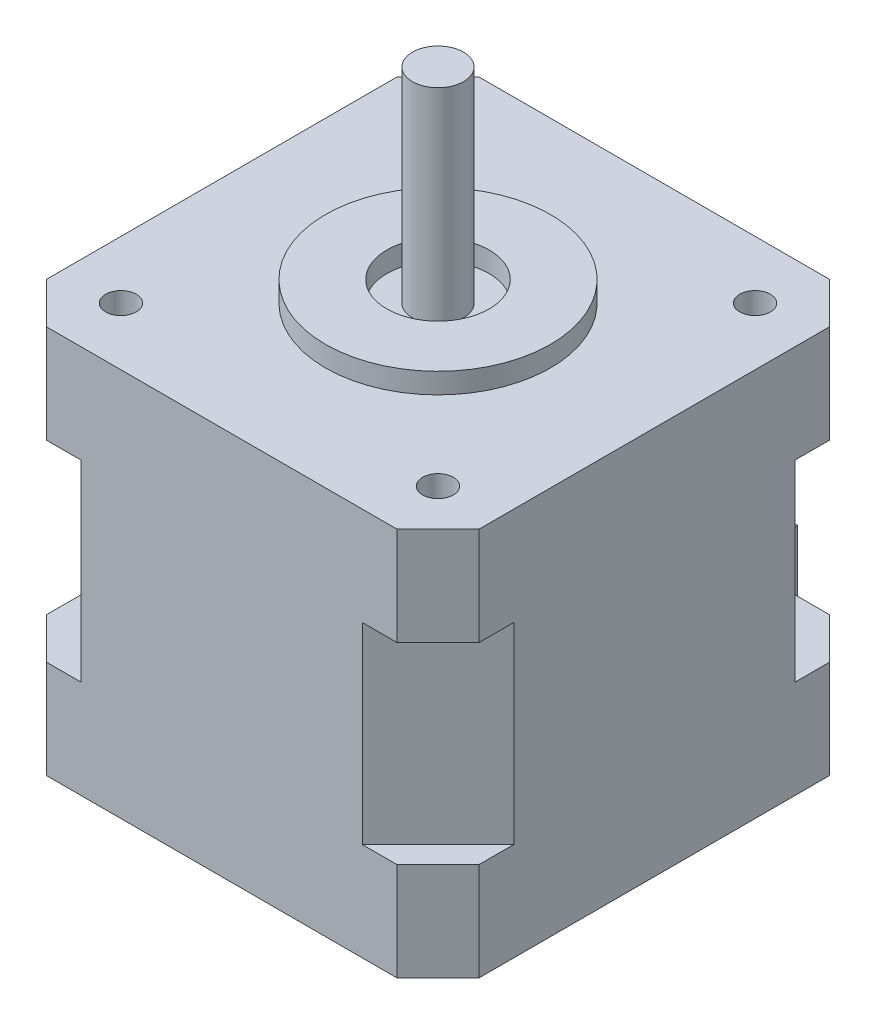
SolidWorks part; units mm, degrees
ref_plane "Front Plane" through (0, 0, 0) normal (0, 0, 1) x (1, 0, 0)
ref_plane "Top Plane" through (0, 0, 0) normal (0, 1, 0) x (1, 0, 0)
ref_plane "Right Plane" through (0, 0, 0) normal (1, 0, 0) x (0, 0, -1)
sketch "Sketch1" plane through (0, 0, 0) normal (0, 1, 0) x (1, 0, 0)
  line L1 (21.15, -21.15) -> (-21.15, -21.15)
  line L2 (21.15, -21.15) -> (21.15, 21.15)
  line L3 (21.15, 21.15) -> (-21.15, 21.15)
  line L4 (-21.15, -21.15) -> (-21.15, 21.15)
  line L5 (21.15, -21.15) -> (-21.15, 21.15) construction
  line L6 (21.15, 21.15) -> (-21.15, -21.15) construction
  point P0 (0, 0)
  dimension "D1" = 42.3
extrude "Boss-Extrude1" add sketch "Sketch1" along normal blind 9.6
chamfer "Chamfer1" distance 4 angle 45 4 edges at (21.15, 4.8, -21.15) (21.15, 4.8, 21.15) (-21.15, 4.8, 21.15) (-21.15, 4.8, -21.15)
sketch "Sketch2" plane through (0, 9.6, 0) normal (0, 1, 0) x (1, 0, 0)
  line L29 (-17.15, -21.15) -> (17.15, -21.15) construction
  line L31 (13.75, -21.15) -> (21.15, -13.7432)
  line L32 (21.15, -17.15) -> (21.15, 17.15) construction
  line L33 (0, 0) -> (0, -21.15) construction
  line L34 (0, 0) -> (-21.15, 0) construction
  line L35 (-21.15, 17.15) -> (-21.15, -17.15) construction
  line L36 (-13.75, -21.15) -> (-21.15, -13.7432)
  line L37 (-13.75, 21.15) -> (-21.15, 13.7432)
  line L38 (13.75, 21.15) -> (21.15, 13.7432)
  line L39 (13.75, -21.15) -> (-13.75, -21.15)
  line L40 (-21.15, -13.7432) -> (-21.15, 13.7432)
  line L41 (-13.75, 21.15) -> (13.75, 21.15)
  line L42 (21.15, 13.7432) -> (21.15, -13.7432)
  dimension "D1" = 13.75
  dimension "D2" = 10.47
extrude "Boss-Extrude2" add sketch "Sketch2" along normal blind 18.8
sketch "Sketch3" plane through (0, 28.4, 0) normal (0, 1, 0) x (1, 0, 0)
  line L8 (17.15, 21.15) -> (-17.15, 21.15)
  line L9 (21.15, 17.15) -> (17.15, 21.15)
  line L10 (21.15, -17.15) -> (21.15, 17.15)
  line L11 (17.15, -21.15) -> (21.15, -17.15)
  line L12 (-17.15, -21.15) -> (17.15, -21.15)
  line L13 (-21.15, -17.15) -> (-17.15, -21.15)
  line L14 (-21.15, 17.15) -> (-21.15, -17.15)
  line L15 (-17.15, 21.15) -> (-21.15, 17.15)
  line L16 (17.15, 21.15) -> (-17.15, 21.15)
  line L17 (21.15, 17.15) -> (17.15, 21.15)
  line L18 (21.15, -17.15) -> (21.15, 17.15)
  line L19 (17.15, -21.15) -> (21.15, -17.15)
  line L20 (-17.15, -21.15) -> (17.15, -21.15)
  line L21 (-21.15, -17.15) -> (-17.15, -21.15)
  line L22 (-21.15, 17.15) -> (-21.15, -17.15)
  line L23 (-17.15, 21.15) -> (-21.15, 17.15)
  dimension "D1" = 0
extrude "Boss-Extrude3" add sketch "Sketch3" along normal blind 9.6
sketch "Sketch4" plane through (0, 38, 0) normal (0, 1, 0) x (1, 0, 0)
  circle A0 centre (0, 0) radius 11
  circle A1 centre (0, 0) radius 5
  dimension "D1" = 22
  dimension "D2" = 10
extrude "Boss-Extrude4" add sketch "Sketch4" along normal blind 2
sketch "Sketch5" plane through (0, 38, 0) normal (0, 1, 0) x (1, 0, 0)
  circle A0 centre (0, 0) radius 2.5
extrude "Boss-Extrude5" add sketch "Sketch5" along normal blind 20
sketch "Sketch8" plane through (0, 38, 0) normal (0, 1, 0) x (1, 0, 0)
  line L0 (0, -23.2651) -> (0, 23.2651) construction
  line L1 (-23.2651, 0) -> (23.2651, 0) construction
  circle A0 centre (15.5, -15.5) radius 1.5
  dimension "D3" = 3
  dimension "D1" = 15.5
  dimension "D2" = 15.5
extrude "Cut-Extrude1" cut sketch "Sketch8" against normal blind 4
mirror "Mirror1" about plane through (0, 0, 0) normal (0, 0, 1) of "Cut-Extrude1"
mirror "Mirror2" about plane through (0, 0, 0) normal (1, 0, 0) of "Mirror1", "Cut-Extrude1"
ref_plane "Plane1" through (0, 19, 0) normal (0, 1, 0) x (1, 0, 0)
mirror "Mirror3" about plane through (0, 19, 0) normal (0, 1, 0) of "Mirror1", "Cut-Extrude1", "Mirror2"
sketch "Sketch9" plane through (0, 0, -21.15) normal (0, 0, -1) x (-1, 0, 0)
  line L0 (0, 23.2651) -> (0, -23.2651) construction
  line L1 (-8, 0) -> (8, 0)
  line L2 (-8, 0) -> (-8, 9.6)
  line L3 (-8, 9.6) -> (8, 9.6)
  line L4 (8, 0) -> (8, 9.6)
  dimension "D2" = 8
extrude "Boss-Extrude6" add sketch "Sketch9" along normal blind 4
sketch "Sketch10" plane through (0, 0, -25.15) normal (0, 0, -1) x (-1, 0, 0)
  line L0 (8, 0) -> (8, 9.6) construction
  line L1 (-8, 9.6) -> (8, 9.6)
  line L2 (-8, 9.6) -> (-8, 3.2)
  line L3 (-8, 3.2) -> (8, 3.2)
  line L4 (8, 9.6) -> (8, 3.2)
  dimension "D1" = 6.4
extrude "Boss-Extrude7" add sketch "Sketch10" along normal blind 2
sketch "Sketch11" plane through (0, 0, -27.15) normal (0, 0, -1) x (-1, 0, 0)
  line L8 (-7.5, 9.1) -> (-7.5, 3.7)
  line L9 (-7.5, 3.7) -> (7.5, 3.7)
  line L10 (7.5, 3.7) -> (7.5, 9.1)
  line L11 (7.5, 9.1) -> (-7.5, 9.1)
  line L12 (-7.5, 9.1) -> (-7.5, 3.7)
  line L13 (-7.5, 3.7) -> (7.5, 3.7)
  line L14 (7.5, 3.7) -> (7.5, 9.1)
  line L15 (7.5, 9.1) -> (-7.5, 9.1)
  dimension "D1" = 0.5
extrude "Cut-Extrude2" cut sketch "Sketch11" against normal blind 4
